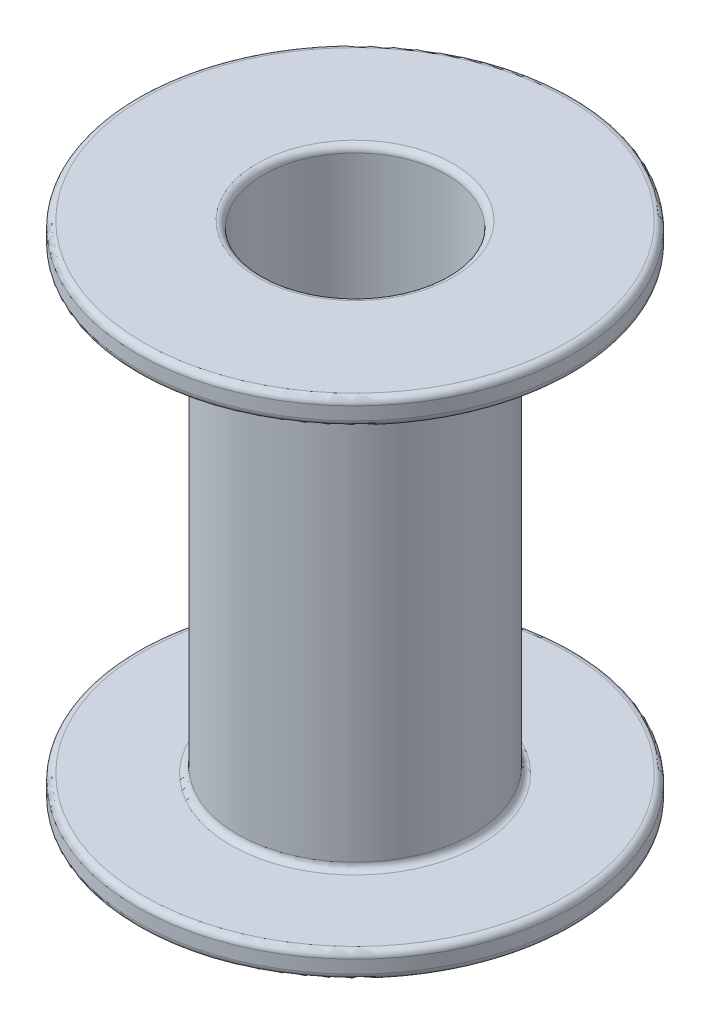
SolidWorks part; units mm, degrees
ref_plane "Front Plane" through (0, 0, 0) normal (0, 0, 1) x (1, 0, 0)
ref_plane "Top Plane" through (0, 0, 0) normal (0, 1, 0) x (1, 0, 0)
ref_plane "Right Plane" through (0, 0, 0) normal (1, 0, 0) x (0, 0, -1)
sketch "Sketch1" plane through (0, 0, 0) normal (0, 1, 0) x (1, 0, 0)
  circle A0 centre (0, 0) radius 16.865
  dimension "D1" = 33.73
extrude "Boss-Extrude1" add sketch "Sketch1" along normal blind 39.05
sketch "Sketch2" plane through (0, 39.05, 0) normal (0, 1, 0) x (1, 0, 0)
  circle A0 centre (0, 0) radius 7.1
  dimension "D1" = 14.2
extrude "Cut-Extrude1" cut sketch "Sketch2" against normal through all contours A0
shell "Shell5" thickness 2
fillet "Fillet1" radius 0.5 8 edges at (0, 0, 7.1) (0, 39.05, 7.1) (0, 2, 16.865) (0, 0, 16.865) (0, 37.05, 16.865) (0, 39.05, 16.865) (0, 37.05, 9.1) (0, 2, 9.1)
